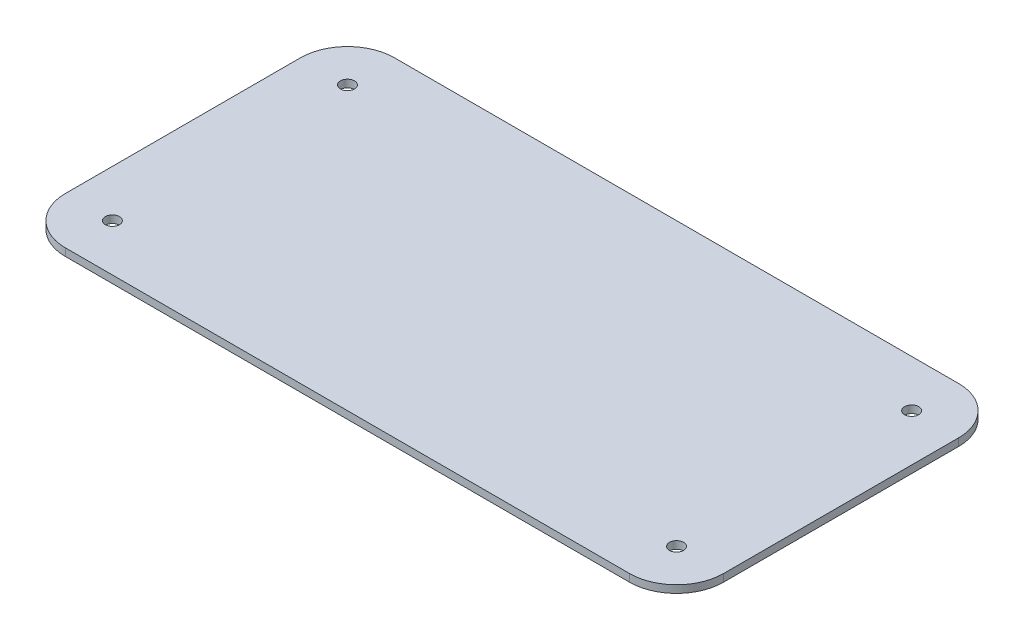
SolidWorks part; units mm, degrees
material "PW80:Mi:0:41:Ar:0:-1:C1:1:2:3:Re:15:"
ref_plane "Plan1" through (0, 0, 0) normal (0, 0, 1) x (1, 0, 0)
ref_plane "Plan2" through (0, 0, 0) normal (0, 1, 0) x (1, 0, 0)
ref_plane "Plan3" through (0, 0, 0) normal (1, 0, 0) x (0, 0, -1)
sketch "Esquisse1" plane through (0, 0, 0) normal (0, 1, 0) x (1, 0, 0)
  line L1 (50, 0) -> (650, 0)
  line L2 (0, 50) -> (0, 300)
  line L3 (50, 350) -> (650, 350)
  line L4 (700, 50) -> (700, 300)
  arc A0 (0, 50) -> (50, 0) centre (50, 50) ccw
  arc A1 (50, 350) -> (0, 300) centre (50, 300) ccw
  arc A2 (700, 300) -> (650, 350) centre (650, 300) ccw
  arc A3 (650, 0) -> (700, 50) centre (650, 50) ccw
  point P7 (0, 0)
  dimension "D1" = 50
extrude "Base-Extrusion" add sketch "Esquisse1" along normal blind 8
sketch "Esquisse2" plane through (0, 8, 0) normal (0, 1, 0) x (-1, 0, 0)
  circle A0 centre (-50, -50) radius 7.5
  circle A1 centre (-50, -300) radius 7.5
  circle A2 centre (-650, -50) radius 7.5
  circle A3 centre (-650, -300) radius 7.5
extrude "Enlèv. mat.-Extru.1" cut sketch "Esquisse2" against normal blind 8
